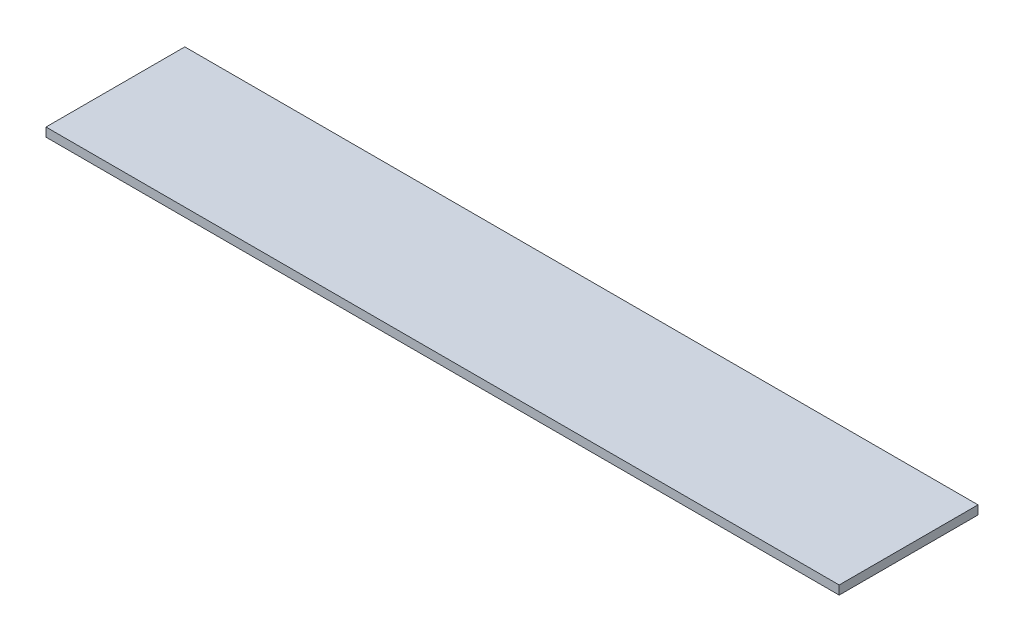
SolidWorks part; units mm, degrees
ref_plane "Front Plane" through (0, 0, 0) normal (0, 0, 1) x (1, 0, 0)
ref_plane "Top Plane" through (0, 0, 0) normal (0, 1, 0) x (1, 0, 0)
ref_plane "Right Plane" through (0, 0, 0) normal (1, 0, 0) x (0, 0, -1)
sketch "Sketch1" plane through (0, 0, 0) normal (0, 1, 0) x (1, 0, 0)
  line L1 (-261.0837, 173.4233) -> (119.9163, 173.4233)
  line L2 (-261.0837, 173.4233) -> (-261.0837, -207.5767)
  line L3 (-261.0837, -207.5767) -> (119.9163, -207.5767)
  line L4 (119.9163, 173.4233) -> (119.9163, -207.5767)
  dimension "D1" = 381
  dimension "D2" = 381
extrude "Boss-Extrude1" add sketch "Sketch1" along normal blind 25.4
fillet "Fillet1" radius 25.4 4 edges at (-261.0837, 12.7, -173.4233) (-261.0837, 12.7, 207.5767) (119.9163, 12.7, 207.5767) (119.9163, 12.7, -173.4233)
sketch "Sketch2" plane through (0, 25.4, 0) normal (0, 1, 0) x (1, 0, 0)
  line L0 (94.5163, 173.4233) -> (-235.6837, 173.4233) construction
  line L1 (-261.0837, 148.0233) -> (-261.0837, -182.1767) construction
  line L2 (-70.5837, 173.4233) -> (-70.5837, -207.5767) construction
  line L3 (-235.6837, -207.5767) -> (94.5163, -207.5767) construction
  line L4 (119.9163, -17.0767) -> (-261.0837, -17.0767) construction
  line L5 (119.9163, -182.1767) -> (119.9163, 148.0233) construction
  line L6 (119.9163, -182.1767) -> (119.9163, 148.0233)
  line L7 (94.5163, 173.4233) -> (-235.6837, 173.4233)
  line L8 (110.3569, 127.9428) -> (74.4359, 163.8639)
  line L9 (74.4359, 163.8639) -> (89.8833, 163.8639)
  line L10 (110.3569, 127.9428) -> (110.3569, 143.3902)
  line L11 (-251.5242, 127.9428) -> (-251.5242, 143.3902)
  line L12 (-215.6032, 163.8639) -> (-231.0506, 163.8639)
  line L13 (-251.5242, -162.0962) -> (-251.5242, -177.5436)
  line L14 (-215.6032, -198.0173) -> (-231.0506, -198.0173)
  line L15 (110.3569, -162.0962) -> (74.4359, -198.0173)
  line L16 (110.3569, -162.0962) -> (110.3569, -177.5436)
  line L17 (74.4359, -198.0173) -> (89.8833, -198.0173)
  arc A0 (-223.3269, 163.8639) -> (-251.5242, 135.6665) centre (-227.0386, 139.3782) ccw
  arc A2 (75.1102, 173.4233) -> (119.9163, 128.6172) centre (112.4768, 165.9838) ccw
  arc A3 (-216.2776, 173.4233) -> (-261.0837, 128.6172) centre (-253.6442, 165.9838) cw
  arc A4 (-223.3269, -198.0173) -> (-251.5242, -169.8199) centre (-227.0386, -173.5316) cw
  arc A5 (119.9163, 148.0233) -> (94.5163, 173.4233) centre (94.5163, 148.0233) ccw construction
  arc A6 (119.9163, 148.0233) -> (94.5163, 173.4233) centre (94.5163, 148.0233) ccw
  circle A8 centre (112.4768, 165.9838) radius 38.1
  arc A11 (82.1596, 163.8639) -> (110.3569, 135.6665) centre (85.8712, 139.3782) cw
  arc A12 (-216.2776, -207.5767) -> (-261.0837, -162.7706) centre (-253.6442, -200.1372) ccw
  arc A13 (82.1596, -198.0173) -> (110.3569, -169.8199) centre (85.8712, -173.5316) ccw
  arc A14 (75.1102, -207.5767) -> (119.9163, -162.7706) centre (112.4768, -200.1372) cw
  dimension "D1" = 50.8
  dimension "D2" = 135
extrude "Boss-Extrude2" add sketch "Sketch2" along normal blind 127
fillet "Fillet5" radius 2.54 4 edges at (119.9163, 88.9, -128.6172) (110.3569, 88.9, -127.9428) (74.4359, 88.9, -163.8639) (75.1102, 88.9, -173.4233)
fillet "Fillet6" radius 2.54 12 edges at (-215.6032, 88.9, -163.8639) (-216.2776, 88.9, -173.4233) (-251.5242, 88.9, -127.9428) (-261.0837, 88.9, -128.6172) (-216.2776, 88.9, 207.5767) (-215.6032, 88.9, 198.0173) (-261.0837, 88.9, 162.7706) (-251.5242, 88.9, 162.0962) (74.4359, 88.9, 198.0173) (75.1102, 88.9, 207.5767) (110.3569, 88.9, 162.0962) (119.9163, 88.9, 162.7706)
sketch "Sketch3" plane through (0, 152.4, 0) normal (0, 1, 0) x (1, 0, 0)
  line L0 (-261.0837, -164.9164) -> (-261.0837, -182.1767) construction
  line L1 (-261.0837, -207.5767) -> (119.9163, -207.5767)
  line L2 (-261.0837, -207.5767) -> (-261.0837, -162.0399)
  line L3 (-261.0837, -162.0399) -> (119.9163, -162.0399)
  line L4 (119.9163, -207.5767) -> (119.9163, -162.0399)
  line L5 (-235.6837, -207.5767) -> (-218.4233, -207.5767) construction
  dimension "D1" = 381
extrude "Boss-Extrude3" add sketch "Sketch3" along normal blind 127
sketch "Sketch5" plane through (0, 152.4, 0) normal (0, -1, 0) x (1, 0, 0)
  line L0 (-261.0837, 162.0399) -> (-261.0837, 164.9164) construction
  line L1 (-254.0942, 162.0399) -> (-261.0837, 162.0399) construction
  line L2 (-261.0837, 207.5767) -> (-235.6837, 207.5767) construction
  line L3 (-261.0837, 182.1767) -> (-261.0837, 207.5767) construction
  line L4 (-261.0837, 162.0399) -> (-261.0837, 164.9164)
  line L5 (-254.0942, 162.0399) -> (-261.0837, 162.0399)
  line L6 (-261.0837, 207.5767) -> (-235.6837, 207.5767)
  line L7 (-261.0837, 182.1767) -> (-261.0837, 207.5767)
  arc A0 (-261.0837, 164.9164) -> (-258.8936, 162.4006) centre (-258.5437, 164.9164) ccw construction
  arc A1 (-258.8936, 162.4006) -> (-254.0942, 162.0399) centre (-253.6442, 200.1372) ccw construction
  arc A2 (-235.6837, 207.5767) -> (-261.0837, 182.1767) centre (-235.6837, 182.1767) ccw construction
  arc A3 (-261.0837, 164.9164) -> (-258.8936, 162.4006) centre (-258.5437, 164.9164) ccw
  arc A4 (-258.8936, 162.4006) -> (-254.0942, 162.0399) centre (-253.6442, 200.1372) ccw
  arc A5 (-235.6837, 207.5767) -> (-261.0837, 182.1767) centre (-235.6837, 182.1767) ccw
extrude "Cut-Extrude1" cut sketch "Sketch5" against normal blind 127
sketch "Sketch6" plane through (0, 152.4, 0) normal (0, -1, 0) x (1, 0, 0)
  line L0 (119.9163, 162.0399) -> (112.9269, 162.0399) construction
  line L1 (119.9163, 164.9164) -> (119.9163, 162.0399) construction
  line L2 (119.9163, 207.5767) -> (119.9163, 182.1767) construction
  line L3 (94.5163, 207.5767) -> (119.9163, 207.5767) construction
  line L4 (119.9163, 162.0399) -> (112.9269, 162.0399)
  line L5 (119.9163, 164.9164) -> (119.9163, 162.0399)
  line L6 (119.9163, 207.5767) -> (119.9163, 182.1767)
  line L7 (94.5163, 207.5767) -> (119.9163, 207.5767)
  arc A0 (112.9269, 162.0399) -> (117.7263, 162.4006) centre (112.4768, 200.1372) ccw construction
  arc A1 (117.7263, 162.4006) -> (119.9163, 164.9164) centre (117.3763, 164.9164) ccw construction
  arc A2 (119.9163, 182.1767) -> (94.5163, 207.5767) centre (94.5163, 182.1767) ccw construction
  arc A3 (112.9269, 162.0399) -> (117.7263, 162.4006) centre (112.4768, 200.1372) ccw
  arc A4 (117.7263, 162.4006) -> (119.9163, 164.9164) centre (117.3763, 164.9164) ccw
  arc A5 (119.9163, 182.1767) -> (94.5163, 207.5767) centre (94.5163, 182.1767) ccw
extrude "Cut-Extrude2" cut sketch "Sketch6" against normal blind 127
sketch "Sketch7" plane through (0, 0, 207.5767) normal (0, 0, 1) x (1, 0, 0)
  line L0 (-218.4233, 152.4) -> (77.256, 152.4) construction
  line L1 (-197.3962, 152.4) -> (-356.9891, 152.4)
  line L2 (-197.3962, 152.4) -> (-197.3962, -127.2684)
  line L3 (-197.3962, -127.2684) -> (-356.9891, -127.2684)
  line L4 (-356.9891, 152.4) -> (-356.9891, -127.2684)
  line L6 (-197.3962, 152.4) -> (188.2054, 152.4)
  line L7 (-197.3962, 152.4) -> (-197.3962, -138.9301)
  line L8 (-197.3962, -138.9301) -> (188.2054, -138.9301)
  line L9 (188.2054, 152.4) -> (188.2054, -138.9301)
extrude "Cut-Extrude3" cut sketch "Sketch7" against normal through all contours L6 L3 L0 L2 L8 L4 | L2 L0 L3 | L9 L6 L4 L8 L2 L7 | L1 L4 L3 L2 L8 L7 | L2 L0 L1 L7 L8 | L2 L1 L0
sketch "Sketch9" plane through (0, 279.4, 0) normal (0, 1, 0) x (1, 0, 0)
  line L4 (112.9269, -162.0399) -> (-254.0942, -162.0399)
  line L5 (-261.0837, -164.9164) -> (-261.0837, -182.1767)
  line L6 (-235.6837, -207.5767) -> (94.5163, -207.5767)
  line L7 (119.9163, -182.1767) -> (119.9163, -164.9164)
  line L8 (112.9269, -162.0399) -> (-254.0942, -162.0399)
  line L9 (-261.0837, -164.9164) -> (-261.0837, -182.1767)
  line L10 (-235.6837, -207.5767) -> (94.5163, -207.5767)
  line L11 (119.9163, -182.1767) -> (119.9163, -164.9164)
  arc A6 (119.9163, -164.9164) -> (117.7263, -162.4006) centre (117.3763, -164.9164) ccw
  arc A7 (117.7263, -162.4006) -> (112.9269, -162.0399) centre (112.4768, -200.1372) ccw
  arc A8 (-254.0942, -162.0399) -> (-258.8936, -162.4006) centre (-253.6442, -200.1372) ccw
  arc A9 (-258.8936, -162.4006) -> (-261.0837, -164.9164) centre (-258.5437, -164.9164) ccw
  arc A10 (-261.0837, -182.1767) -> (-235.6837, -207.5767) centre (-235.6837, -182.1767) ccw
  arc A11 (94.5163, -207.5767) -> (119.9163, -182.1767) centre (94.5163, -182.1767) ccw
  arc A12 (119.9163, -164.9164) -> (117.7263, -162.4006) centre (117.3763, -164.9164) ccw
  arc A13 (117.7263, -162.4006) -> (112.9269, -162.0399) centre (112.4768, -200.1372) ccw
  arc A14 (-254.0942, -162.0399) -> (-258.8936, -162.4006) centre (-253.6442, -200.1372) ccw
  arc A15 (-258.8936, -162.4006) -> (-261.0837, -164.9164) centre (-258.5437, -164.9164) ccw
  arc A16 (-261.0837, -182.1767) -> (-235.6837, -207.5767) centre (-235.6837, -182.1767) ccw
  arc A17 (94.5163, -207.5767) -> (119.9163, -182.1767) centre (94.5163, -182.1767) ccw
  dimension "D1" = 0
extrude "Cut-Extrude4" cut sketch "Sketch9" against normal blind 121.92
sketch "Sketch10" plane through (0, 157.48, 0) normal (0, 1, 0) x (1, 0, 0)
  line L0 (112.9269, -162.0399) -> (-254.0942, -162.0399) construction
  line L1 (-248.2533, -162.0399) -> (-261.0837, -162.0399)
  line L2 (-248.2533, -162.0399) -> (-248.2533, -167.4209)
  line L3 (-248.2533, -167.4209) -> (-261.0837, -167.4209)
  line L4 (-261.0837, -162.0399) -> (-261.0837, -167.4209)
  line L5 (-261.0837, -164.9164) -> (-261.0837, -182.1767) construction
  line L6 (119.9163, -182.1767) -> (119.9163, -164.9164) construction
  line L7 (107.7264, -162.0399) -> (119.9163, -162.0399)
  line L8 (107.7264, -162.0399) -> (107.7264, -169.5931)
  line L9 (107.7264, -169.5931) -> (119.9163, -169.5931)
  line L10 (119.9163, -162.0399) -> (119.9163, -169.5931)
extrude "Boss-Extrude4" add sketch "Sketch10" against normal blind 5.08
sketch "Sketch12" plane through (0, 0, 162.0399) normal (0, 0, -1) x (-1, 0, 0)
  line L0 (261.0837, 152.4) -> (261.0837, 157.48) construction
  line L1 (-119.9163, 157.48) -> (261.0837, 157.48) construction
  line L2 (-119.9163, 152.4) -> (-119.9163, 157.48) construction
  line L3 (-119.9163, 152.4) -> (261.0837, 152.4) construction
  line L4 (261.0837, 152.4) -> (261.0837, 157.48)
  line L5 (-119.9163, 157.48) -> (261.0837, 157.48)
  line L6 (-119.9163, 152.4) -> (-119.9163, 157.48)
  line L7 (-119.9163, 152.4) -> (261.0837, 152.4)
extrude "Boss-Extrude5" add sketch "Sketch12" along normal blind 5.842
sketch "Sketch13" plane through (0, 157.48, 0) normal (0, 1, 0) x (1, 0, 0)
  line L4 (-235.6837, -207.5767) -> (94.5163, -207.5767)
  line L5 (119.9163, -182.1767) -> (119.9163, -156.1979)
  line L6 (119.9163, -156.1979) -> (-261.0837, -156.1979)
  line L7 (-261.0837, -156.1979) -> (-261.0837, -182.1767)
  line L9 (119.9163, -182.1767) -> (119.9163, -156.1979)
  line L10 (119.9163, -156.1979) -> (-261.0837, -156.1979)
  line L11 (-261.0837, -156.1979) -> (-261.0837, -182.1767)
  line L12 (-235.6837, -207.5767) -> (94.5163, -207.5767)
  arc A2 (-261.0837, -182.1767) -> (-235.6837, -207.5767) centre (-235.6837, -182.1767) ccw
  arc A3 (-261.0837, -182.1767) -> (-235.6837, -207.5767) centre (-235.6837, -182.1767) ccw
  arc A4 (94.5163, -207.5767) -> (119.9163, -182.1767) centre (94.5163, -182.1767) ccw
  arc A5 (94.5163, -207.5767) -> (119.9163, -182.1767) centre (94.5163, -182.1767) ccw
  dimension "D1" = 0
sketch "Sketch14" plane through (0, 157.48, 0) normal (0, 1, 0) x (1, 0, 0)
  line L1 (119.9163, -182.1767) -> (94.5163, -182.1767)
  line L2 (119.9163, -182.1767) -> (119.9163, -207.5767)
  line L3 (119.9163, -207.5767) -> (94.5163, -207.5767)
  line L4 (94.5163, -182.1767) -> (94.5163, -207.5767)
  line L5 (-235.6837, -207.5767) -> (-261.0837, -207.5767)
  line L6 (-235.6837, -207.5767) -> (-235.6837, -182.1767)
  line L7 (-235.6837, -182.1767) -> (-261.0837, -182.1767)
  line L8 (-261.0837, -207.5767) -> (-261.0837, -182.1767)
extrude "Boss-Extrude6" add sketch "Sketch14" against normal up to surface (5.08 mm away) up to face at (-70.5837, 152.4, 183.7373)
sketch "Sketch15" plane through (0, 157.48, 0) normal (0, 1, 0) x (1, 0, 0)
  line L0 (-261.0837, -156.1979) -> (-261.0837, -207.5767) construction
  line L1 (119.9163, -207.5767) -> (-261.0837, -207.5767)
  line L2 (119.9163, -207.5767) -> (119.9163, -182.1767)
  line L3 (119.9163, -182.1767) -> (-261.0837, -182.1767)
  line L4 (-261.0837, -207.5767) -> (-261.0837, -182.1767)
  dimension "D1" = 25.4
extrude "Boss-Extrude7" add sketch "Sketch15" along normal blind 2.54
sketch "Sketch18" plane through (-261.0837, 0, 0) normal (-1, 0, 0) x (0, 0, 1)
  line L1 (182.1767, 157.48) -> (156.1979, 157.48)
  line L2 (182.1767, 157.48) -> (182.1767, 152.4)
  line L3 (182.1767, 152.4) -> (156.1979, 152.4)
  line L4 (156.1979, 157.48) -> (156.1979, 152.4)
extrude "Cut-Extrude6" cut sketch "Sketch18" against normal through all
sketch "Sketch19" plane through (-261.0837, 0, 0) normal (-1, 0, 0) x (0, 0, 1)
  line L0 (207.5767, 152.4) -> (207.5767, 160.02) construction
  line L2 (182.1767, 154.94) -> (182.1767, 149.86)
  line L3 (182.1767, 149.86) -> (207.5767, 149.86)
  line L4 (207.5767, 154.94) -> (207.5767, 149.86)
  line L5 (207.5767, 154.94) -> (182.1767, 154.94)
  line L6 (207.5767, 149.86) -> (182.1767, 149.86)
  line L7 (207.5767, 149.86) -> (207.5767, 152.4)
  line L8 (207.5767, 152.4) -> (182.1767, 152.4)
  line L9 (182.1767, 149.86) -> (182.1767, 152.4)
  line M2 (182.1767, 160.02) -> (182.1767, 152.4)
  line M3 (182.1767, 152.4) -> (207.5767, 152.4)
  line M4 (207.5767, 152.4) -> (207.5767, 160.02)
extrude "Cut-Extrude7" cut sketch "Sketch19" against normal through all contours L5 M4 M2 M3
sketch "Sketch21" plane through (0, 160.02, 0) normal (0, 1, 0) x (1, 0, 0)
  line L1 (-261.0837, -182.1767) -> (-337.2837, -182.1767)
  line L2 (-261.0837, -182.1767) -> (-261.0837, -207.5767)
  line L3 (-261.0837, -207.5767) -> (-337.2837, -207.5767)
  line L4 (-337.2837, -182.1767) -> (-337.2837, -207.5767)
  dimension "D1" = 76.2
extrude "Boss-Extrude8" add sketch "Sketch21" against normal up to surface (5.08 mm away) up to face at (-70.5837, 154.94, 194.8767)
sketch "Sketch22" plane through (0, 0, 182.1767) normal (0, 0, -1) x (-1, 0, 0)
  line L4 (-119.9163, 160.02) -> (-119.9163, 154.94)
  line L5 (-119.9163, 154.94) -> (337.2837, 154.94)
  line L6 (337.2837, 154.94) -> (337.2837, 160.02)
  line L7 (337.2837, 160.02) -> (-119.9163, 160.02)
  line L8 (-119.9163, 160.02) -> (-119.9163, 154.94)
  line L9 (-119.9163, 154.94) -> (337.2837, 154.94)
  line L10 (337.2837, 154.94) -> (337.2837, 160.02)
  line L11 (337.2837, 160.02) -> (-119.9163, 160.02)
  dimension "D1" = 0
extrude "Boss-Extrude9" add sketch "Sketch22" along normal blind 54.61
